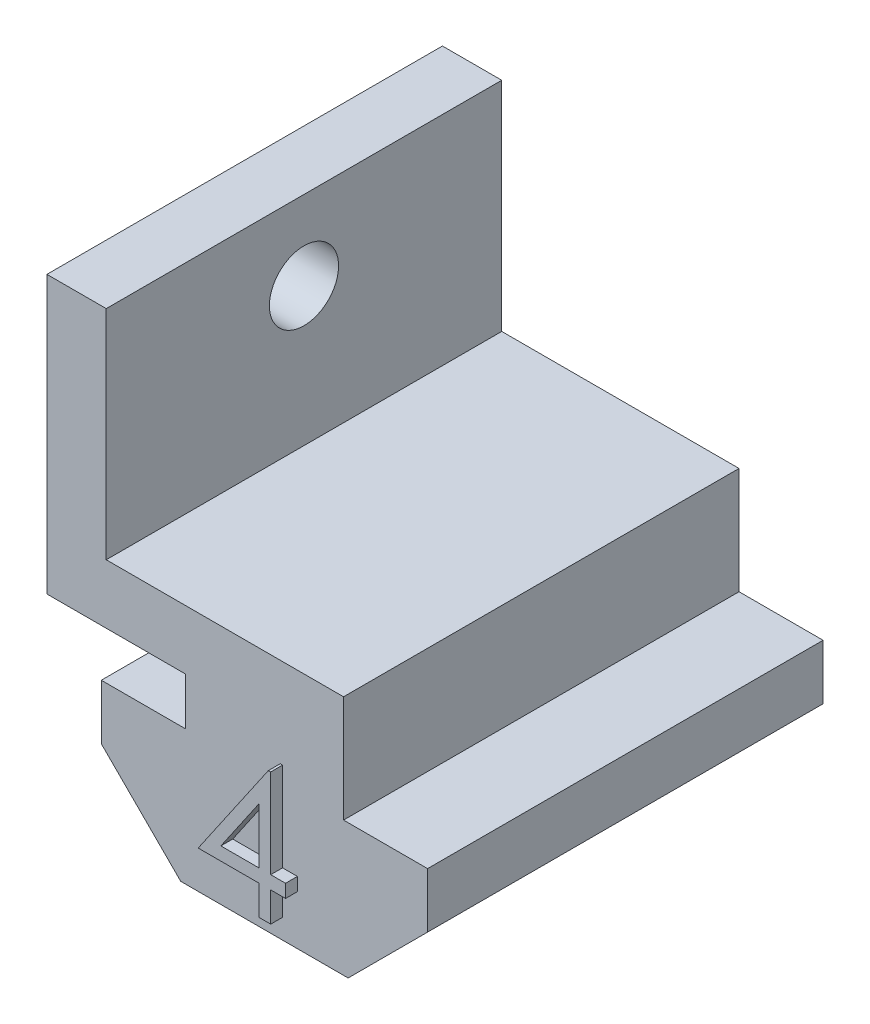
SolidWorks part; units mm, degrees
ref_plane "Piano frontale" through (0, 0, 0) normal (0, 0, 1) x (1, 0, 0)
ref_plane "Piano superiore" through (0, 0, 0) normal (0, 1, 0) x (1, 0, 0)
ref_plane "Piano destro" through (0, 0, 0) normal (1, 0, 0) x (0, 0, -1)
sketch "Schizzo2" plane through (0, 0, 0) normal (0, 0, 1) x (1, 0, 0)
  line L0 (0, 0) -> (0, 12.9875) construction
  line L1 (-4, 9.2) -> (-11, 9.2)
  line L2 (-11, 9.2) -> (-11, 23.2)
  line L3 (-11, 23.2) -> (-8, 23.2)
  line L4 (-8, 23.2) -> (-8, 12.2)
  line L5 (-8, 12.2) -> (4, 12.2)
  line L6 (4, 12.2) -> (4, 9.2)
  line L13 (-4.2322, 0) -> (4.2322, 0)
  line L14 (-8.25, 4.0178) -> (-4.2322, 0)
  line L15 (-8.25, 6.8) -> (-8.25, 4.0178)
  line L16 (-4, 6.8) -> (-8.25, 6.8)
  line L17 (-4, 9.2) -> (-4, 6.8)
  line L44 (8.25, 4.0178) -> (4.2322, 0)
  line L45 (8.25, 6.8) -> (8.25, 4.0178)
  line L46 (4, 6.8) -> (8.25, 6.8)
  line L72 (4, 9.2) -> (4, 6.8)
  dimension "D1" = 8.4645
  dimension "D2" = 4.0178
  dimension "D3" = 2.7822
  dimension "D4" = 8
  dimension "D5" = 2.4
  dimension "D6" = 16.5
  dimension "D7" = 11
  dimension "D8" = 3
  dimension "D9" = 3
  dimension "D10" = 14
extrude "Estrusione-Estrusione1" add sketch "Schizzo2" against normal blind 20
sketch "Schizzo6" plane through (-11, 0, 0) normal (-1, 0, 0) x (0, 0, 1)
  line L0 (0, 23.2) -> (0, 9.2) construction
  line L1 (-20, 23.2) -> (0, 23.2) construction
  circle A0 centre (-10, 19.2) radius 1.75
  dimension "D2" = 3.5
  dimension "D1" = 10
  dimension "D3" = 4
extrude "Taglio-Estrusione1" cut sketch "Schizzo6" against normal up to next
sketch "Schizzo7" plane through (0, 0, 0) normal (0, 0, 1) x (1, 0, 0)
  line L0 (-4.2322, 0) -> (4.2322, 0) construction
  text T0 "4" font "Century Gothic" height 6.5
  dimension "D1" = 1
  dimension "D2" = 3
extrude "Estrusione-Estrusione2" add sketch "Schizzo7" along normal blind 0.6
